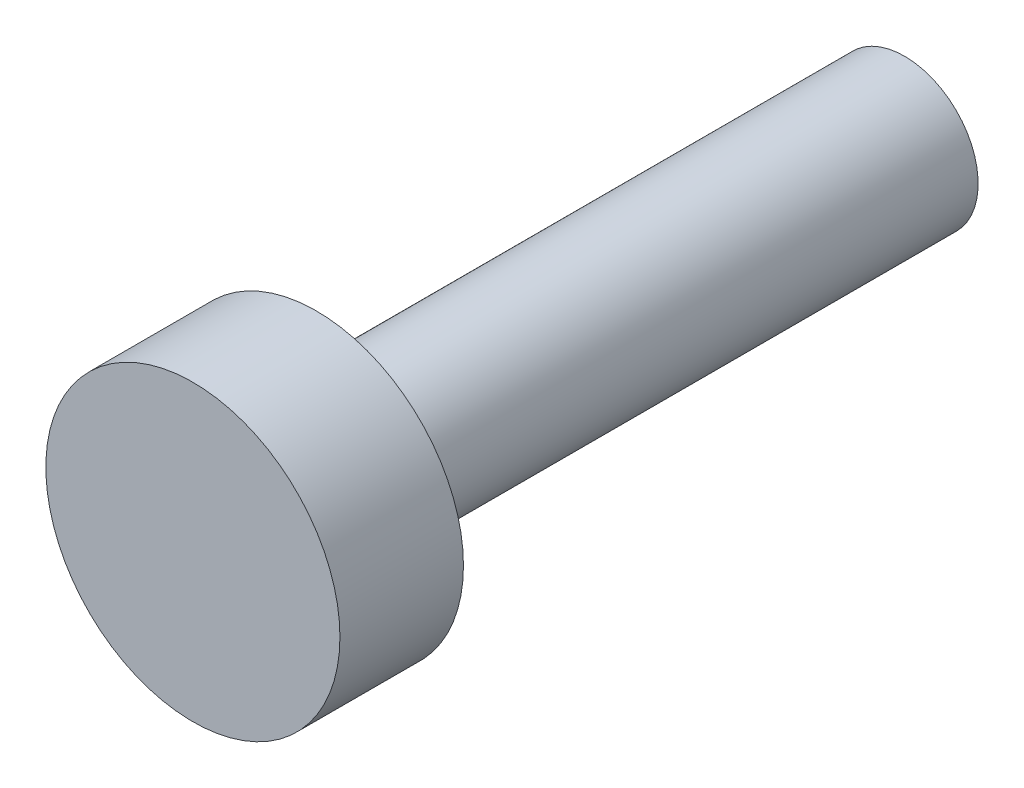
SolidWorks part; units mm, degrees
ref_plane "Plan de face" through (0, 0, 0) normal (0, 0, 1) x (1, 0, 0)
ref_plane "Plan de dessus" through (0, 0, 0) normal (0, 1, 0) x (1, 0, 0)
ref_plane "Plan de droite" through (0, 0, 0) normal (1, 0, 0) x (0, 0, -1)
sketch "Esquisse1" plane through (0, 0, 0) normal (0, 0, 1) x (1, 0, 0)
  circle A0 centre (0, 0) radius 2.5
  dimension "D1" = 5
extrude "Boss.-Extru.1" add sketch "Esquisse1" along normal blind 2.1
sketch "Esquisse2" plane through (0, 0, 0) normal (0, 0, -1) x (-1, 0, 0)
  circle A0 centre (0, 0) radius 1.25
  dimension "D1" = 2.5
extrude "Boss.-Extru.2" add sketch "Esquisse2" along normal blind 10
